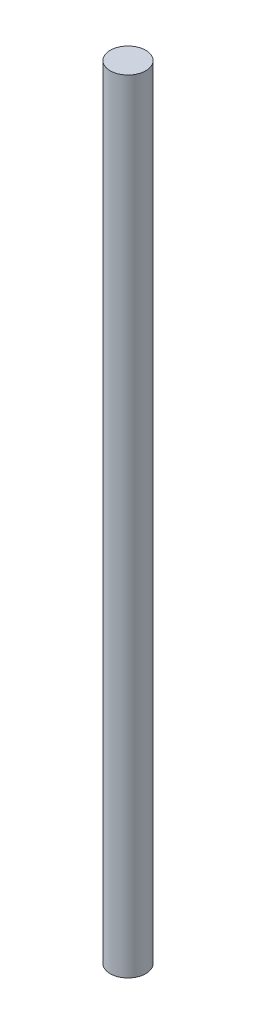
SolidWorks part; units mm, degrees
ref_plane "Ebene vorne" through (0, 0, 0) normal (0, 0, 1) x (1, 0, 0)
ref_plane "Ebene oben" through (0, 0, 0) normal (0, 1, 0) x (1, 0, 0)
ref_plane "Ebene rechts" through (0, 0, 0) normal (1, 0, 0) x (0, 0, -1)
sketch "Skizze1" plane through (0, 0, 0) normal (0, 1, 0) x (1, 0, 0)
  circle A0 centre (0, 0) radius 2.5
  dimension "D1" = 5
extrude "Aufsatz-Linear austragen1" add sketch "Skizze1" against normal blind 110
